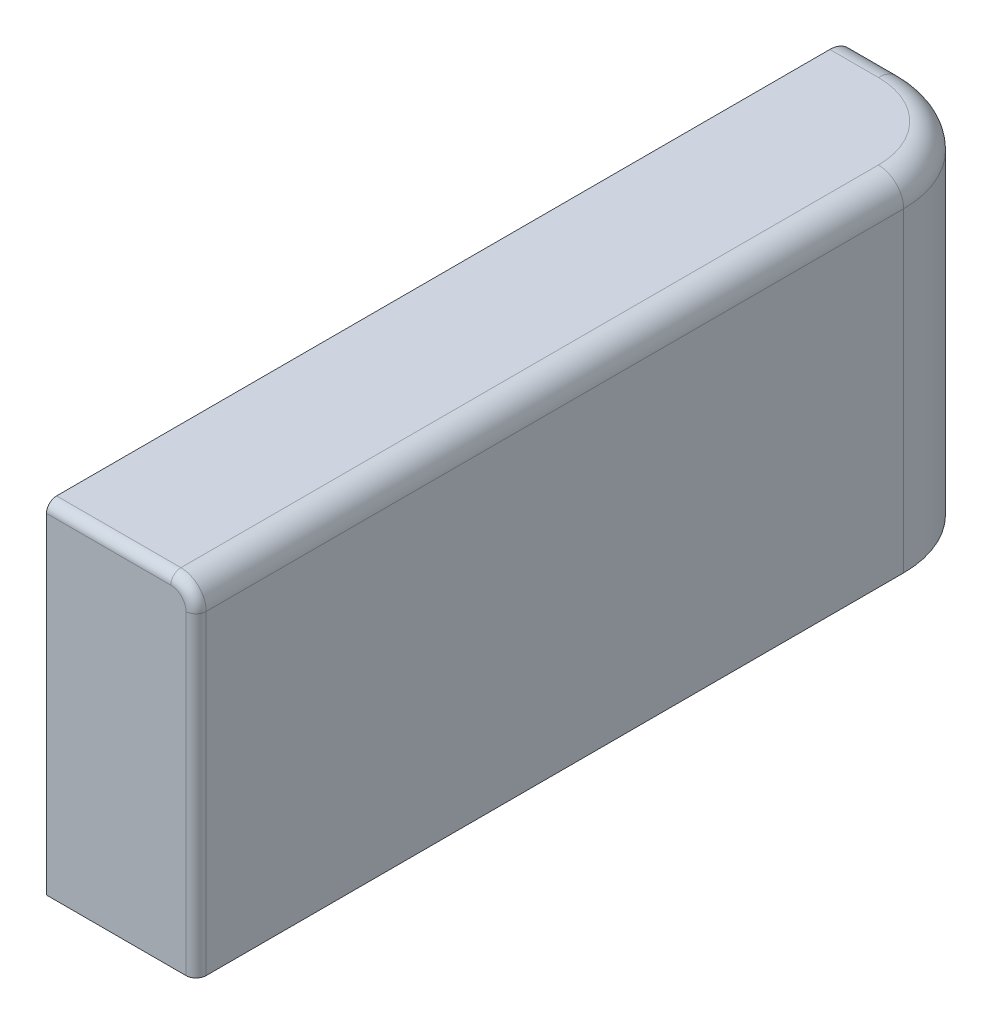
SolidWorks part; units mm, degrees
ref_plane "정면" through (0, 0, 0) normal (0, 0, 1) x (1, 0, 0)
ref_plane "윗면" through (0, 0, 0) normal (0, 1, 0) x (1, 0, 0)
ref_plane "우측면" through (0, 0, 0) normal (1, 0, 0) x (0, 0, -1)
sketch "스케치1" plane through (0, 0, 0) normal (0, 1, 0) x (1, 0, 0)
  line L0 (0, 0) -> (0, 800)
  line L1 (0, 800) -> (48, 800)
  line L2 (148, 700) -> (148, 0)
  line L3 (148, 0) -> (0, 0)
  arc A0 (148, 700) -> (48, 800) centre (48, 700) ccw
  point P7 (148, 800)
  dimension "D3" = 100
  dimension "D1" = 800
  dimension "D2" = 148
extrude "보스-돌출1" add sketch "스케치1" along normal blind 337
fillet "필렛1" radius 25 3 edges at (148, 337, -350) (24, 337, -800) (118.7107, 337, -770.7107)
fillet "필렛2" radius 10 3 edges at (148, 156, 0) (140.6777, 329.6777, 0) (61.5, 337, 0)
shell "쉘1" [suppressed] thickness 3
sketch "스케치2" plane through (0, 0, 0) normal (0, 0, 1) x (1, 0, 0)
  line L0 (138, 30) -> (138, 312)
  line L1 (0, 0) -> (138, 0) construction
  line L2 (30, 30) -> (138, 30)
  line L3 (0, 327) -> (0, 0) construction
  line L4 (148, 312) -> (148, 0) construction
  line L5 (30, 327) -> (123, 327)
  line L6 (30, 327) -> (30, 30)
  line L7 (0, 337) -> (123, 337) construction
  arc A0 (138, 312) -> (123, 327) centre (123, 312) ccw
  dimension "D1" = 10
  dimension "D2" = 30
  dimension "D3" = 30
  dimension "D4" = 10
extrude "컷-돌출1" [suppressed] cut sketch "스케치2" against normal blind 337
sketch "스케치3" plane through (0, 337, 0) normal (0, 1, 0) x (1, 0, 0)
  line L0 (-128.6172, 560) -> (403.0818, 560)
  line L1 (50, 560) -> (50, 530)
  line L2 (0, 480) -> (-120.3354, 480)
  line L3 (-120.3354, 480) -> (188.9445, 480)
  line L4 (0, 775) -> (0, 10) construction
  line L5 (50, 530) -> (50, 680)
  line L7 (0, 730) -> (0, 480)
  arc A0 (0, 480) -> (50, 530) centre (0, 530) ccw
  arc A1 (50, 680) -> (0, 730) centre (0, 680) ccw
  point P11 (50, 480)
  line M5 (0, 775) -> (0, 10)
  dimension "D4" = 50
  dimension "D1" = 560
  dimension "D2" = 80
  dimension "D5" = 150
extrude "컷-돌출2" [suppressed] cut sketch "스케치3" against normal blind 100 contours L5 A1 L0 M5 | A0 L1 L0 M5
sketch "스케치6" plane through (0, 0, 0) normal (0, 0, 1) x (1, 0, 0)
  line L6 (0, 327) -> (0, 0)
  line L7 (0, 0) -> (138, 0)
  line L8 (138, 0) -> (138, 312)
  line L11 (123, 327) -> (0, 327)
  line L12 (0, 327) -> (0, 0)
  line L13 (0, 0) -> (138, 0)
  line L14 (138, 0) -> (138, 312)
  line L17 (123, 327) -> (0, 327)
  arc A4 (138, 312) -> (123, 327) centre (123, 312) ccw
  arc A5 (138, 312) -> (123, 327) centre (123, 312) ccw
  dimension "D1" = 0
extrude "컷-돌출3" [suppressed] cut sketch "스케치6" against normal blind 10
sketch "스케치7" plane through (0, 337, 0) normal (0, 1, 0) x (1, 0, 0)
  circle A0 centre (0, 0) radius 60
  dimension "D1" = 120
extrude "컷-돌출4" [suppressed] cut sketch "스케치7" against normal blind 10
